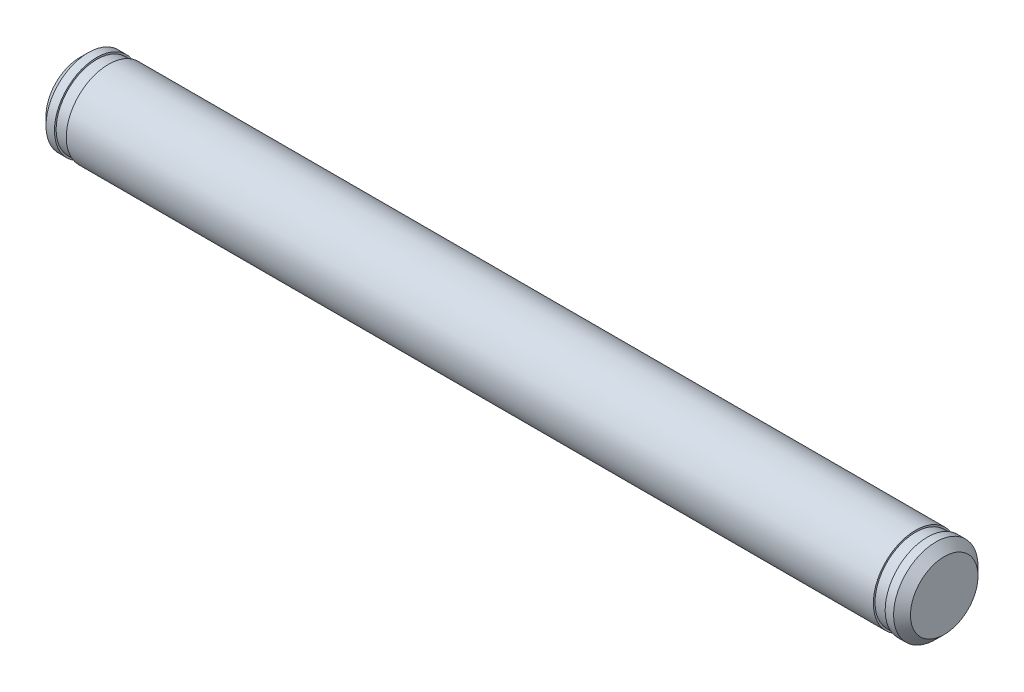
SolidWorks part; units mm, degrees
ref_plane "前视基准面" through (0, 0, 0) normal (0, 0, 1) x (1, 0, 0)
ref_plane "上视基准面" through (0, 0, 0) normal (0, 1, 0) x (1, 0, 0)
ref_plane "右视基准面" through (0, 0, 0) normal (1, 0, 0) x (0, 0, -1)
other "Configuration Table"
sketch "草图1" plane through (0, 0, 0) normal (0, 0, 1) x (1, 0, 0)
  line L0 (-0.2254, 0) -> (25.6, 0) construction
  line L1 (25.6, 0) -> (25.6, 2.5)
  line L2 (25.6, 2.5) -> (24.6, 2.5)
  line L3 (24.6, 2.5) -> (24.6, 2.4)
  line L4 (24.6, 2.4) -> (23.9, 2.4)
  line L5 (23.9, 2.4) -> (23.9, 2.5)
  line L6 (23.9, 2.5) -> (-23.9, 2.5)
  line L7 (0, 2.5) -> (0, 0) construction
  line L8 (0.2254, 0) -> (-25.6, 0) construction
  line L9 (-25.6, 0) -> (-25.6, 2.5)
  line L10 (-23.9, 2.4) -> (-23.9, 2.5)
  line L11 (-24.6, 2.4) -> (-23.9, 2.4)
  line L12 (-24.6, 2.5) -> (-24.6, 2.4)
  line L13 (-25.6, 2.5) -> (-24.6, 2.5)
  line L14 (25.6, 0) -> (-25.6, 0)
  line L15 (24, 2.4) -> (24, 0) construction
  line L16 (-24, 2.4) -> (-24, 0) construction
  dimension "D1" = 5
  dimension "D2" = 4.8
  dimension "D3" = 0.7
  dimension "D4" = 1
  dimension "D5" = 0.6
  dimension "D6" = 48
revolve "旋转1" add sketch "草图1" angle 360 about L14
chamfer "倒角1" distance 0.5 angle 45 2 edges at (25.6, 2.5, 0) (-25.6, 2.5, 0)
ref_plane "基准面1" through (-24, 0, 0) normal (-1, 0, 0) x (0, 0, 1)
